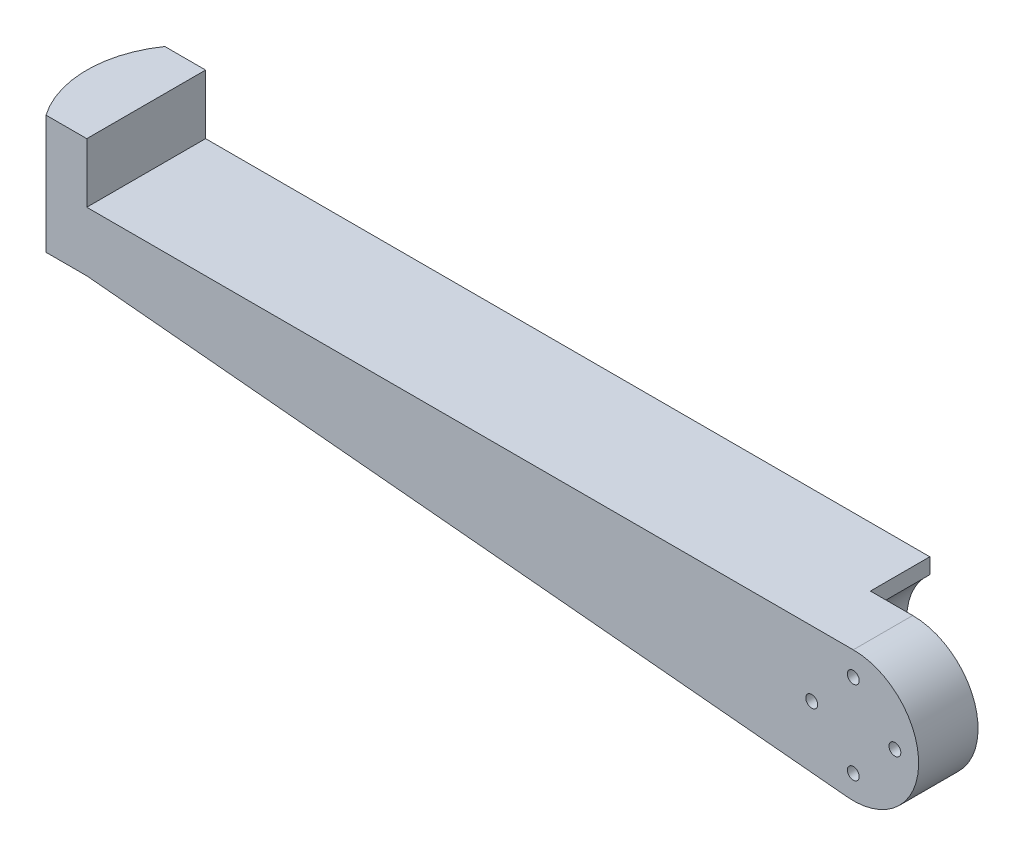
SolidWorks part; units mm, degrees
ref_plane "Front Plane" through (0, 0, 0) normal (0, 0, 1) x (1, 0, 0)
ref_plane "Top Plane" through (0, 0, 0) normal (0, 1, 0) x (1, 0, 0)
ref_plane "Right Plane" through (0, 0, 0) normal (1, 0, 0) x (0, 0, -1)
sketch "Sketch1" plane through (0, 0, 0) normal (0, 0, 1) x (1, 0, 0)
  circle A0 centre (0, 0) radius 11
  circle A1 centre (0, 0) radius 7 construction
  circle A2 centre (0, 7) radius 1
  circle A3 centre (7, 0) radius 1
  circle A4 centre (0, -7) radius 1
  circle A5 centre (-7, 0) radius 1
  dimension "D1" = 22
  dimension "D2" = 14
  dimension "D3" = 2
  dimension "D4" = 4
extrude "Boss-Extrude1" add sketch "Sketch1" along normal blind 10
sketch "Sketch2" plane through (0, 0, 10) normal (0, 0, 1) x (1, 0, 0)
  line L0 (0, 11) -> (-129, 11)
  line L1 (-129, 11) -> (-129, 21)
  line L2 (-129, 21) -> (-139, 21)
  line L3 (-139, 21) -> (-139, 1)
  line L4 (-139, 1) -> (-129, 1)
  line L5 (-129, 1) -> (-1.0229, -10.9523)
  circle A0 centre (0, 0) radius 11 construction
  arc A1 (0, 11) -> (-1.0229, -10.9523) centre (0, 0) ccw
  point P4 (0, 0)
  point P10 (0, 0)
  point P11 (0, 0)
  dimension "D1" = 10
  dimension "D2" = 20
  dimension "D3" = 10
  dimension "D4" = 129
extrude "Boss-Extrude2" add sketch "Sketch2" against normal blind 20
sketch "Sketch3" plane through (0, 0, -10) normal (0, 0, -1) x (-1, 0, 0)
  line L0 (0, 11) -> (7.1226, 11)
  line L1 (0, 11) -> (129, 11) construction
  line L2 (7.1226, 11) -> (7.1226, 8.3827)
  line L3 (7.1226, 8.3827) -> (7.1226, -8.3827) construction
  line L4 (7.1226, -8.3827) -> (7.1226, -10.3827)
  line L5 (129, 1) -> (1.0229, -10.9523) construction
  line L6 (1.0229, -10.9523) -> (7.1226, -10.3827)
  arc A0 (1.0229, -10.9523) -> (0, 11) centre (0, 0) ccw construction
  arc A1 (1.0229, -10.9523) -> (7.1226, -8.3827) centre (0, 0) ccw
  arc A2 (7.1226, 8.3827) -> (0, 11) centre (0, 0) ccw
  dimension "D1" = 2
extrude "Cut-Extrude2" cut sketch "Sketch3" against normal up to surface (10 mm away) up to face at (0, 0, 0)
sketch "Sketch4" plane through (0, 21, 0) normal (0, 1, 0) x (1, 0, 0)
  line L0 (-139, 10) -> (-139, -10) construction
  line L1 (-135.8614, 10) -> (-139, 10)
  line L2 (-129, 10) -> (-139, 10) construction
  line L3 (-139, 10) -> (-139, 0)
  arc A0 (-135.8614, 10) -> (-139, 0) centre (-121.5, 0) ccw
  point P1 (-80, 0)
  dimension "D1" = 35
extrude "Cut-Extrude3" cut sketch "Sketch4" against normal up to surface (20 mm away) up to face at (-134, 1, 0)
mirror "Mirror1" about plane through (0, 0, 0) normal (0, 0, 1) of "Cut-Extrude3"
